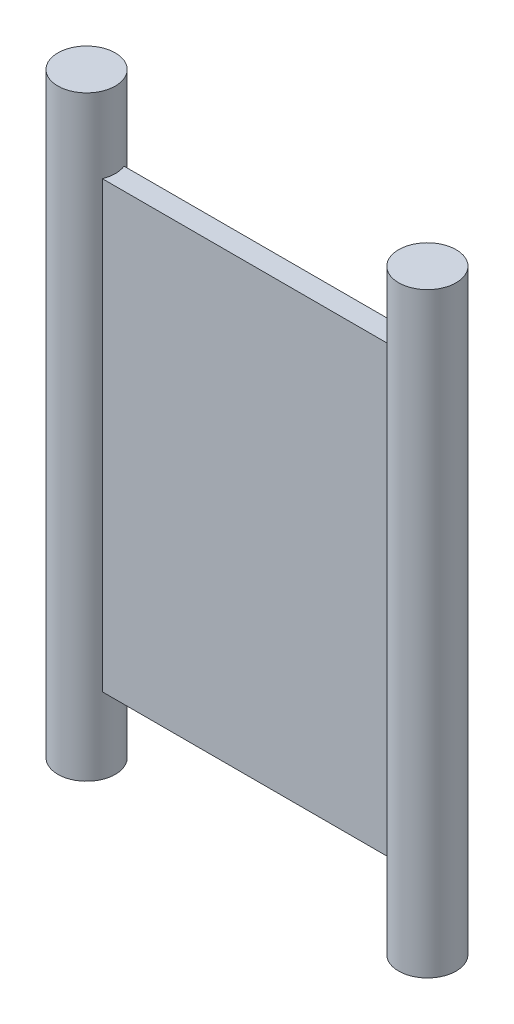
SolidWorks part; units mm, degrees
ref_plane "Front Plane" through (0, 0, 0) normal (0, 0, 1) x (1, 0, 0)
ref_plane "Top Plane" through (0, 0, 0) normal (0, 1, 0) x (1, 0, 0)
ref_plane "Right Plane" through (0, 0, 0) normal (1, 0, 0) x (0, 0, -1)
sketch "Sketch1" plane through (0, 0, 0) normal (0, 1, 0) x (1, 0, 0)
  line L1 (7.86, 0.5) -> (-7.86, 0.5)
  line L2 (7.86, 0.5) -> (7.86, -0.5)
  line L3 (7.86, -0.5) -> (-7.86, -0.5)
  line L4 (-7.86, 0.5) -> (-7.86, -0.5)
  line L5 (7.86, 0.5) -> (-7.86, -0.5) construction
  line L6 (7.86, -0.5) -> (-7.86, 0.5) construction
  point P0 (0, 0)
  dimension "D1" = 15.72
  dimension "D3" = 1
extrude "Boss-Extrude1" add sketch "Sketch1" along normal blind 20.5
ref_plane "Plane1" through (0, 10.25, 0) normal (0, 1, 0) x (1, 0, 0)
sketch "Sketch2" plane through (0, 10.25, 0) normal (0, 1, 0) x (1, 0, 0)
  line L0 (7.86, -0.5) -> (7.86, 0.5) construction
  line L1 (-7.86, 0.5) -> (-7.86, -0.5) construction
  line L2 (7.86, -0.5) -> (7.86, 0.5) construction
  line L3 (-7.86, 0.5) -> (-7.86, -0.5) construction
  circle A0 centre (-7.86, 0) radius 1.325
  circle A1 centre (7.86, 0) radius 1.325
  dimension "D1" = 2.65
extrude "Boss-Extrude2" add sketch "Sketch2" along normal mid plane 27.5
